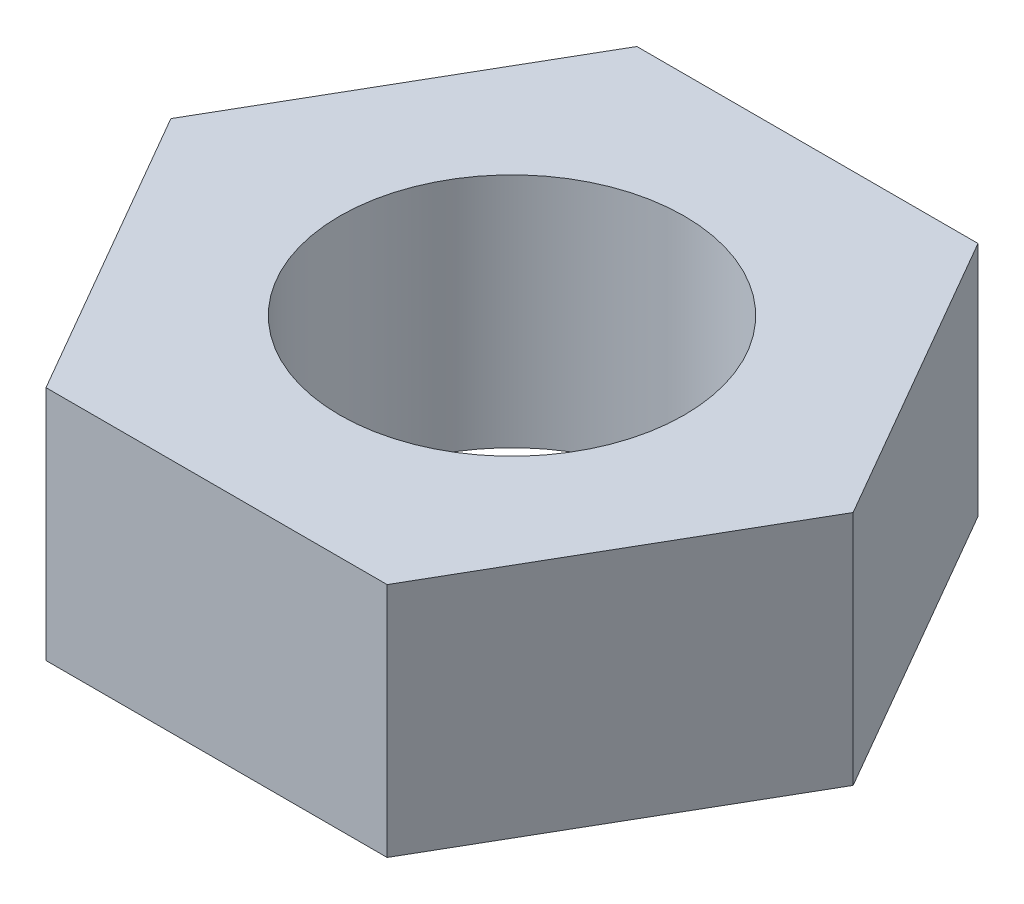
SolidWorks part; units mm, degrees
material "Brass"
ref_plane "Front Plane" through (0, 0, 0) normal (0, 0, 1) x (1, 0, 0)
ref_plane "Top Plane" through (0, 0, 0) normal (0, 1, 0) x (1, 0, 0)
ref_plane "Right Plane" through (0, 0, 0) normal (1, 0, 0) x (0, 0, -1)
sketch "Sketch1" plane through (0, 0, 0) normal (0, 1, 0) x (1, 0, 0)
  line L1 (-10.9985, 0) -> (-5.4993, -9.525)
  line L2 (-5.4993, -9.525) -> (5.4993, -9.525)
  line L3 (5.4993, -9.525) -> (10.9985, 0)
  line L4 (10.9985, 0) -> (5.4993, 9.525)
  line L5 (5.4993, 9.525) -> (-5.4993, 9.525)
  line L6 (-5.4993, 9.525) -> (-10.9985, 0)
  circle A0 centre (0, 0) radius 9.525 construction
  dimension "D1" = 19.05
extrude "Boss-Extrude1" add sketch "Sketch1" along normal blind 7.62
hole_wizard "7/16-20 Tapped Hole1" positions "Sketch3" profile "Sketch2" tap size "7/16-20" standard "ANSI Inch" end condition through all
sketch "Sketch3" plane through (0, 7.62, 0) normal (0, 1, 0) x (1, 0, 0)
  point P0 (0, 0)
sketch "Sketch2" plane through (0, 7.62, 0) normal (1, 0, 0) x (0, 0, 1)
  line L0 (0, 0) -> (0, 7.62)
  line L1 (0, 7.62) -> (5.5562, 7.62)
  line L2 (5.5562, 7.62) -> (5.5562, 0)
  line L5 (5.5562, 0) -> (0, 0)
  line L11 (0, -6.35) -> (0, 107.95) construction
  dimension "Thread Major Dia." = 11.1125
  dimension "Thru Tap Drill Depth" = 7.62
